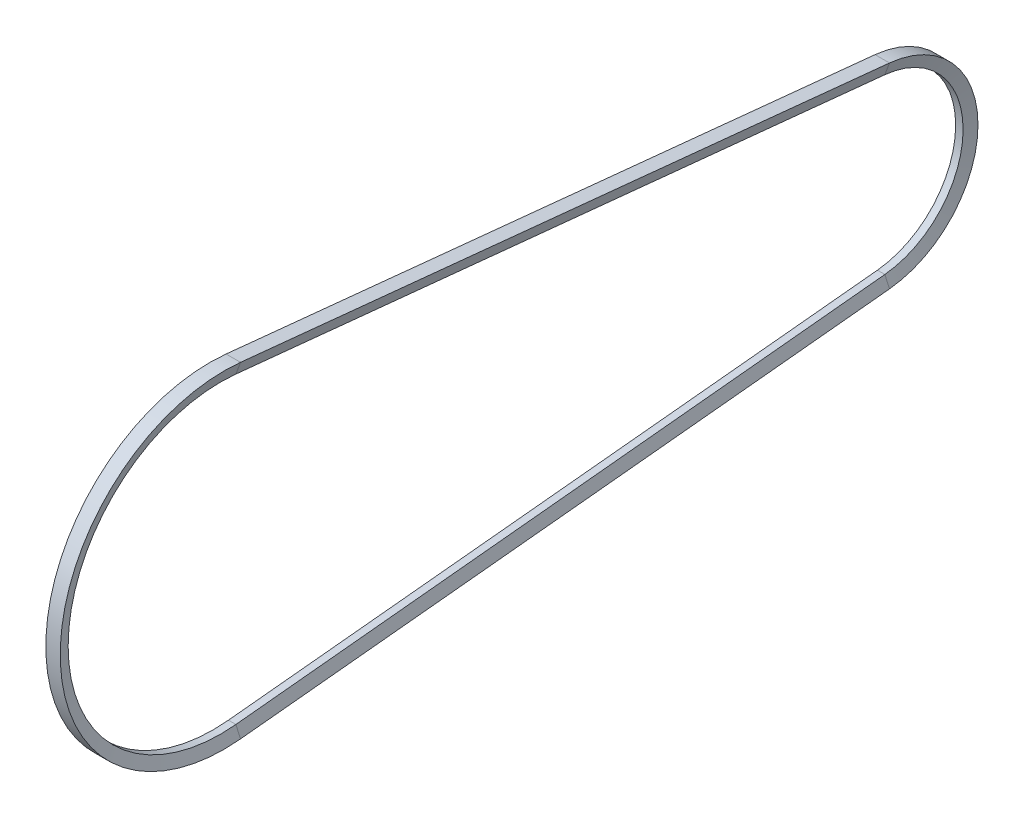
SolidWorks part; units mm, degrees
ref_plane "前视基准面" through (0, 0, 0) normal (0, 0, 1) x (1, 0, 0)
ref_plane "上视基准面" through (0, 0, 0) normal (0, 1, 0) x (1, 0, 0)
ref_plane "右视基准面" through (0, 0, 0) normal (1, 0, 0) x (0, 0, -1)
sketch "草图1" plane through (0, 0, 0) normal (1, 0, 0) x (0, 0, -1)
  line L0 (12.5, 124.3734) -> (507.5, 74.6241)
  line L1 (12.5, -124.3734) -> (507.5, -74.6241)
  line L2 (0, 0) -> (500, 0) construction
  arc A0 (12.5, 124.3734) -> (12.5, -124.3734) centre (0, 0) ccw
  arc A1 (507.5, -74.6241) -> (507.5, 74.6241) centre (500, 0) ccw
  dimension "D1" = 125
  dimension "D2" = 75
  dimension "D3" = 500
sketch "草图2" plane through (0, 0, 0) normal (0, 0, 1) x (1, 0, 0)
  line L0 (-5.5, 125) -> (5.5, 125)
  line L1 (5.5, 125) -> (2.8401, 116.3)
  line L2 (2.8401, 116.3) -> (-2.8401, 116.3)
  line L3 (-2.8401, 116.3) -> (-5.5, 125)
  line L4 (0, 116.3) -> (0, 125) construction
  line L5 (0, -125) -> (0, 125) construction
  dimension "D1" = 11
  dimension "D2" = 8.7
  dimension "D3" = 34
sweep "扫描1" add profiles "草图2" path "草图1"
equation "\"D3@草图1\" = \"D1@距离1@孔板轮_椭圆辐轮.Assembly\""
equation "\"D1@草图2\" = \"bd@草图1@大带轮_椭圆辐轮.Part\" "
equation "\"D2@草图2\" = \"hf@草图1@大带轮_椭圆辐轮.Part\" "
equation "\"D3@草图2\" = \"槽轮角@草图1@大带轮_椭圆辐轮.Part\" "
equation " \"D2@草图1\" = \"dd@草图1@小带轮_孔板轮.Part\"/2"
equation "\"D1@草图1\" = \"dd@草图1@大带轮_椭圆辐轮.Part\" /2"
